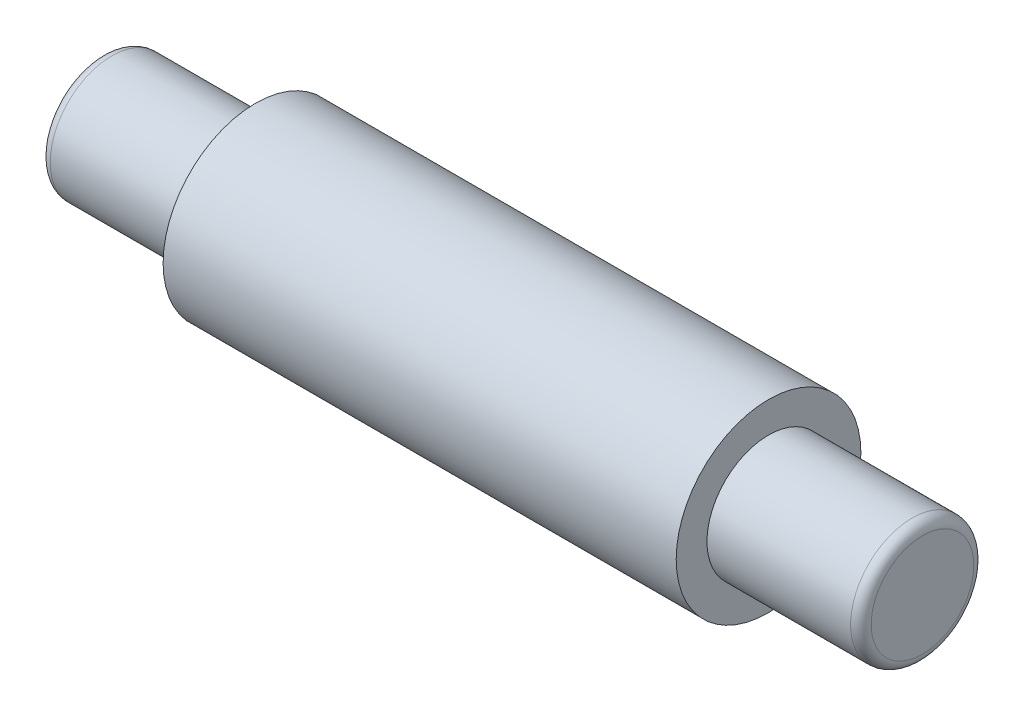
SolidWorks part; units mm, degrees
ref_plane "Front Plane" through (0, 0, 0) normal (0, 0, 1) x (1, 0, 0)
ref_plane "Top Plane" through (0, 0, 0) normal (0, 1, 0) x (1, 0, 0)
ref_plane "Right Plane" through (0, 0, 0) normal (1, 0, 0) x (0, 0, -1)
sketch "Sketch1" plane through (0, 0, 0) normal (1, 0, 0) x (0, 0, -1)
  circle A0 centre (0, 0) radius 9
  dimension "D1" = 18
extrude "Boss-Extrude1" add sketch "Sketch1" along normal blind 50
sketch "Sketch2" plane through (50, 0, 0) normal (1, 0, 0) x (0, 0, -1)
  circle A0 centre (0, 0) radius 6
  dimension "D1" = 12
extrude "Boss-Extrude2" add sketch "Sketch2" along normal blind 15
sketch "Sketch3" plane through (0, 0, 0) normal (-1, 0, 0) x (0, 0, 1)
  circle A0 centre (0, 0) radius 6
extrude "Boss-Extrude3" add sketch "Sketch3" along normal blind 15
fillet "Fillet1" radius 1 1 edges at (-15, 0, 6)
fillet "Fillet2" radius 1 1 edges at (65, 0, -6)
